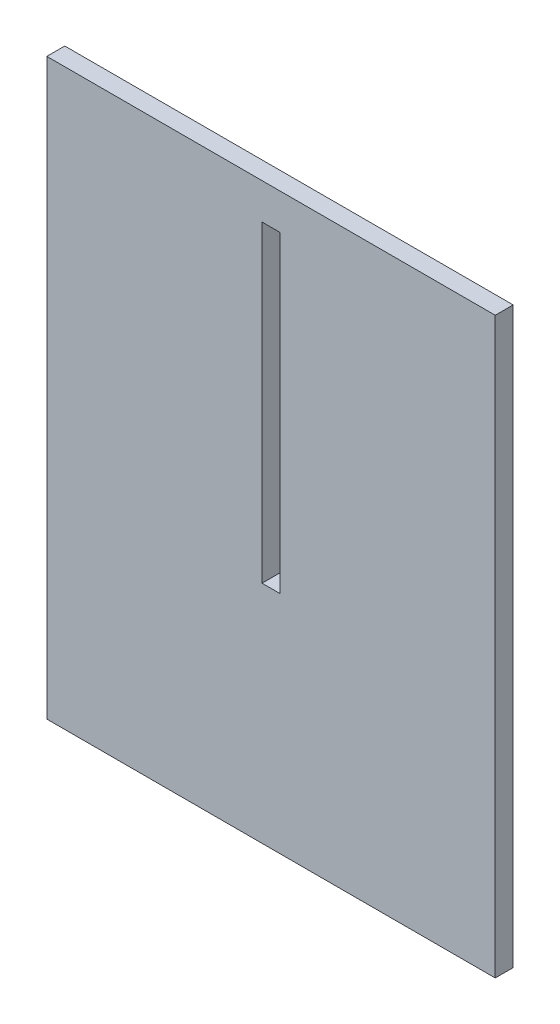
SolidWorks part; units mm, degrees
ref_plane "Front Plane" through (0, 0, 0) normal (0, 0, 1) x (1, 0, 0)
ref_plane "Top Plane" through (0, 0, 0) normal (0, 1, 0) x (1, 0, 0)
ref_plane "Right Plane" through (0, 0, 0) normal (1, 0, 0) x (0, 0, -1)
sketch "Sketch1" plane through (0, 0, 0) normal (0, 0, 1) x (1, 0, 0)
  line L1 (0, 0) -> (125, 0)
  line L2 (0, 0) -> (0, -160)
  line L3 (0, -160) -> (125, -160)
  line L4 (125, 0) -> (125, -160)
  line L5 (60, -10) -> (65, -10)
  line L6 (60, -10) -> (60, -97.1892)
  line L7 (60, -97.1892) -> (65, -97.1892)
  line L8 (65, -10) -> (65, -97.1892)
  dimension "D1" = 125
  dimension "D2" = 160
  dimension "D3" = 5
  dimension "D4" = 60
  dimension "D5" = 10
extrude "Boss-Extrude1" add sketch "Sketch1" along normal blind 5
